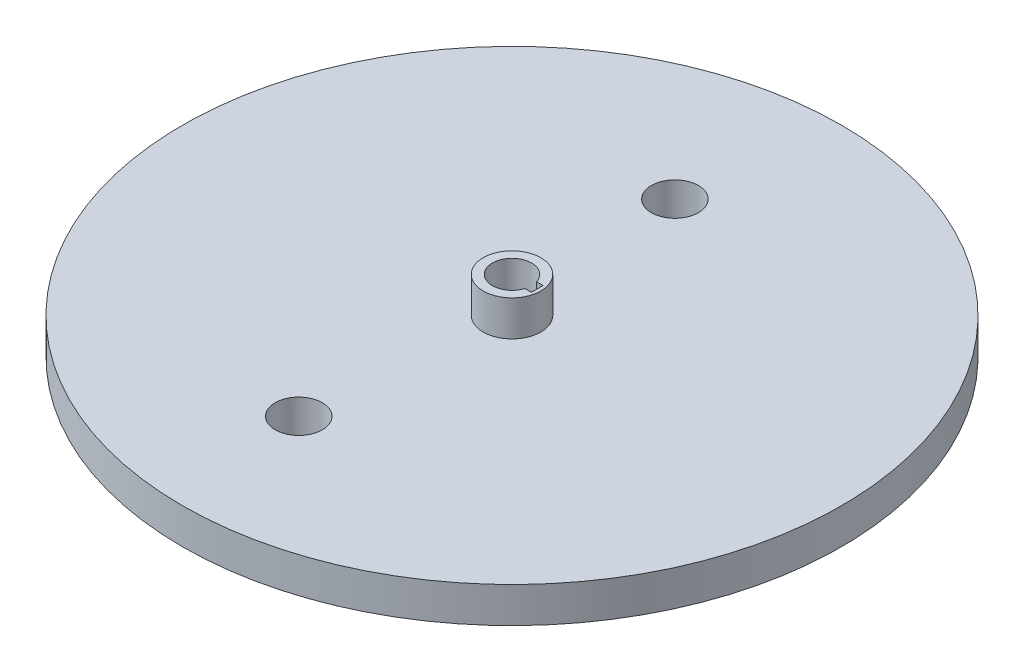
SolidWorks part; units mm, degrees
ref_plane "Front Plane" through (0, 0, 0) normal (0, 0, 1) x (1, 0, 0)
ref_plane "Top Plane" through (0, 0, 0) normal (0, 1, 0) x (1, 0, 0)
ref_plane "Right Plane" through (0, 0, 0) normal (1, 0, 0) x (0, 0, -1)
sketch "Sketch1" plane through (0, 0, 0) normal (0, 1, 0) x (1, 0, 0)
  line L1 (10.74, 0) -> (10.74, 2.5)
  line L2 (10.74, 0) -> (10.74, -2.5)
  line L3 (10.74, 2.5) -> (7.9565, 2.5)
  line L4 (10.74, -2.5) -> (7.9565, -2.5)
  circle A0 centre (0, 0) radius 140
  arc A1 (7.9565, 2.5) -> (7.9565, -2.5) centre (0, 0) ccw
  dimension "D1" = 280
  dimension "D2" = 16.68
extrude "Boss-Extrude1" add sketch "Sketch1" along normal blind 30.25
sketch "Sketch2" plane through (0, 30.25, 0) normal (0, 1, 0) x (1, 0, 0)
  circle A0 centre (0, 0) radius 12.2445
  circle A1 centre (0, 0) radius 36.5
extrude "Cut-Extrude1" cut sketch "Sketch2" against normal blind 15.125
sketch "Sketch3" plane through (0, 15.125, 0) normal (0, 1, 0) x (1, 0, 0)
  circle A0 centre (0, 0) radius 150
  circle A1 centre (0, 0) radius 12.9387
extrude "Cut-Extrude3" cut sketch "Sketch3" along normal blind 60
sketch "Sketch4" plane through (0, 0, 0) normal (0, -1, 0) x (-1, 0, 0)
  circle A0 centre (8.2029, 77.4024) radius 10
  circle A1 centre (8.2029, -82.388) radius 10
extrude "Cut-Extrude4" cut sketch "Sketch4" against normal blind 20
